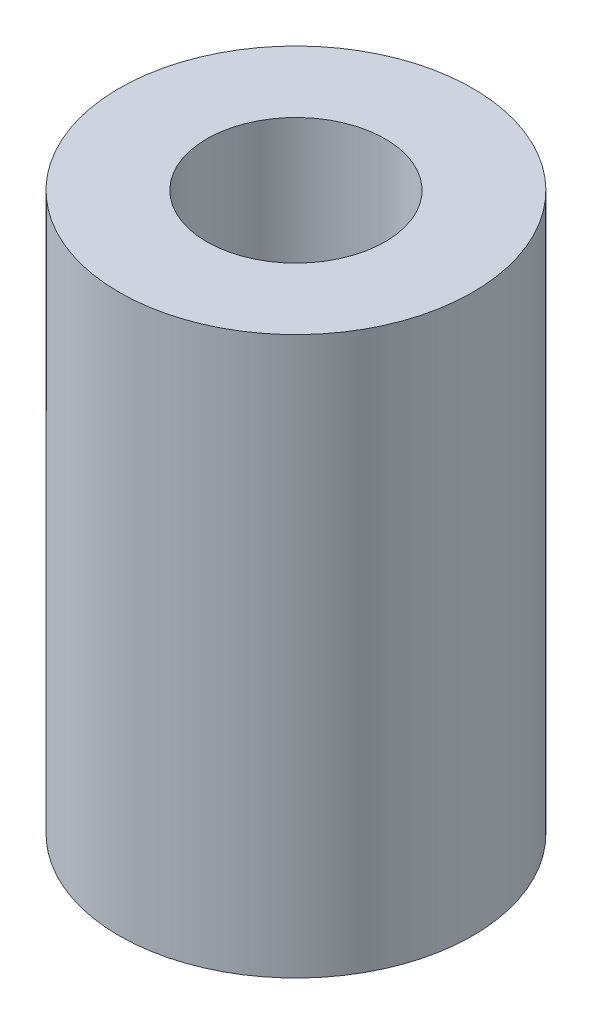
SolidWorks part; units mm, degrees
ref_plane "Front Plane" through (0, 0, 0) normal (0, 0, 1) x (1, 0, 0)
ref_plane "Top Plane" through (0, 0, 0) normal (0, 1, 0) x (1, 0, 0)
ref_plane "Right Plane" through (0, 0, 0) normal (1, 0, 0) x (0, 0, -1)
sketch "Sketch1" plane through (0, 0, 0) normal (0, 1, 0) x (1, 0, 0)
  circle A0 centre (0, 0) radius 7.9756
  circle A1 centre (0, 0) radius 4.0259
  dimension "D1" = 15.9512
  dimension "D2" = 8.0518
extrude "Boss-Extrude1" add sketch "Sketch1" along normal blind 25.146
